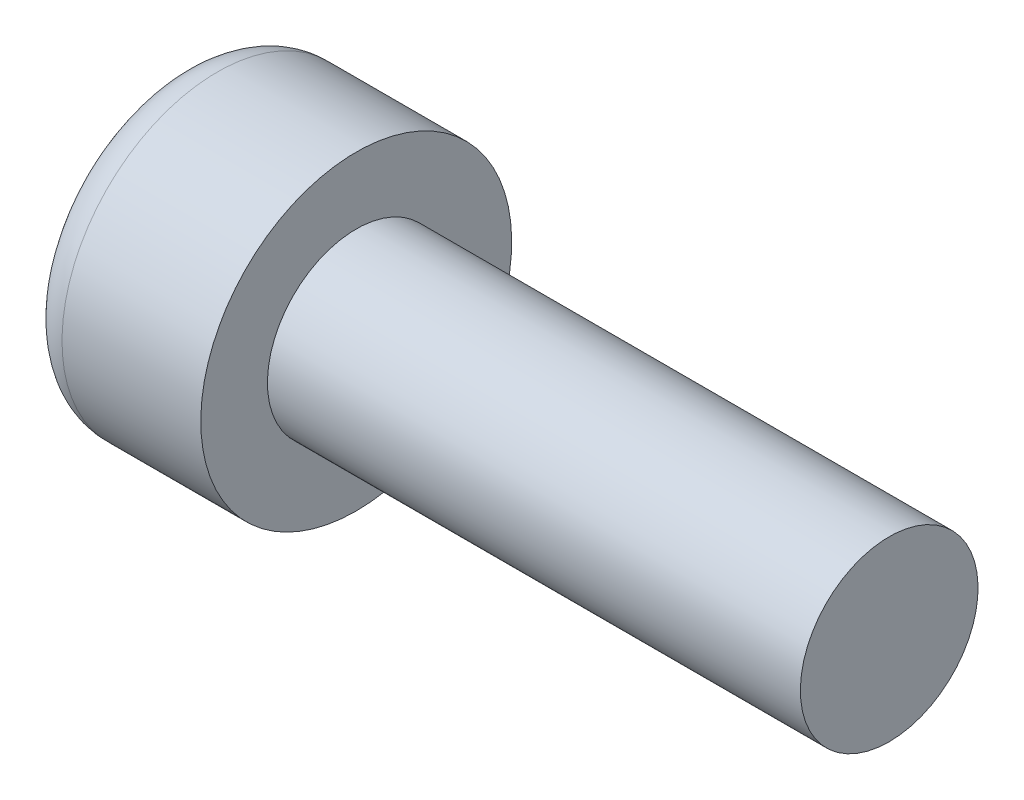
SolidWorks part; units mm, degrees
material "Plain Carbon Steel"
ref_plane "Front Plane" through (0, 0, 0) normal (0, 0, 1) x (1, 0, 0)
ref_plane "Top Plane" through (0, 0, 0) normal (0, 1, 0) x (1, 0, 0)
ref_plane "Right Plane" through (0, 0, 0) normal (1, 0, 0) x (0, 0, -1)
sketch "Sketch1" plane through (0, 0, 0) normal (0, 0, 1) x (1, 0, 0)
  line L0 (0, 0) -> (0, 2.625)
  line L1 (0.875, 3.5) -> (4, 3.5)
  line L2 (4, 3.5) -> (4, 2)
  line L3 (4, 2) -> (16, 2)
  line L4 (16, 2) -> (16, 0)
  line L5 (16, 0) -> (0, 0) construction
  line L6 (0.875, 2.625) -> (0.875, 1.75) construction
  line L7 (0.875, 1.75) -> (0.875, 0.875) construction
  line L8 (0.875, 0.875) -> (0.875, 0) construction
  line L9 (0.875, 3.5) -> (0.875, 2.625) construction
  line L10 (0, 0) -> (16, 0)
  arc A0 (0, 2.625) -> (0.875, 3.5) centre (0.875, 2.625) cw
  dimension "D1" = 4
  dimension "D2" = 7
  dimension "D3" = 4
  dimension "D4" = 12
revolve "Revolve1" add sketch "Sketch1" angle 360 about L10
sketch "Sketch2" plane through (0, 0, 0) normal (-1, 0, 0) x (0, 0, 1)
  line L1 (0, 1.7321) -> (-1.5, 0.866)
  line L2 (-1.5, 0.866) -> (-1.5, -0.866)
  line L3 (-1.5, -0.866) -> (0, -1.7321)
  line L4 (0, -1.7321) -> (1.5, -0.866)
  line L5 (1.5, -0.866) -> (1.5, 0.866)
  line L6 (1.5, 0.866) -> (0, 1.7321)
  circle A0 centre (0, 0) radius 1.5 construction
  dimension "D1" = 3
extrude "Cut-Extrude1" cut sketch "Sketch2" against normal blind 2
